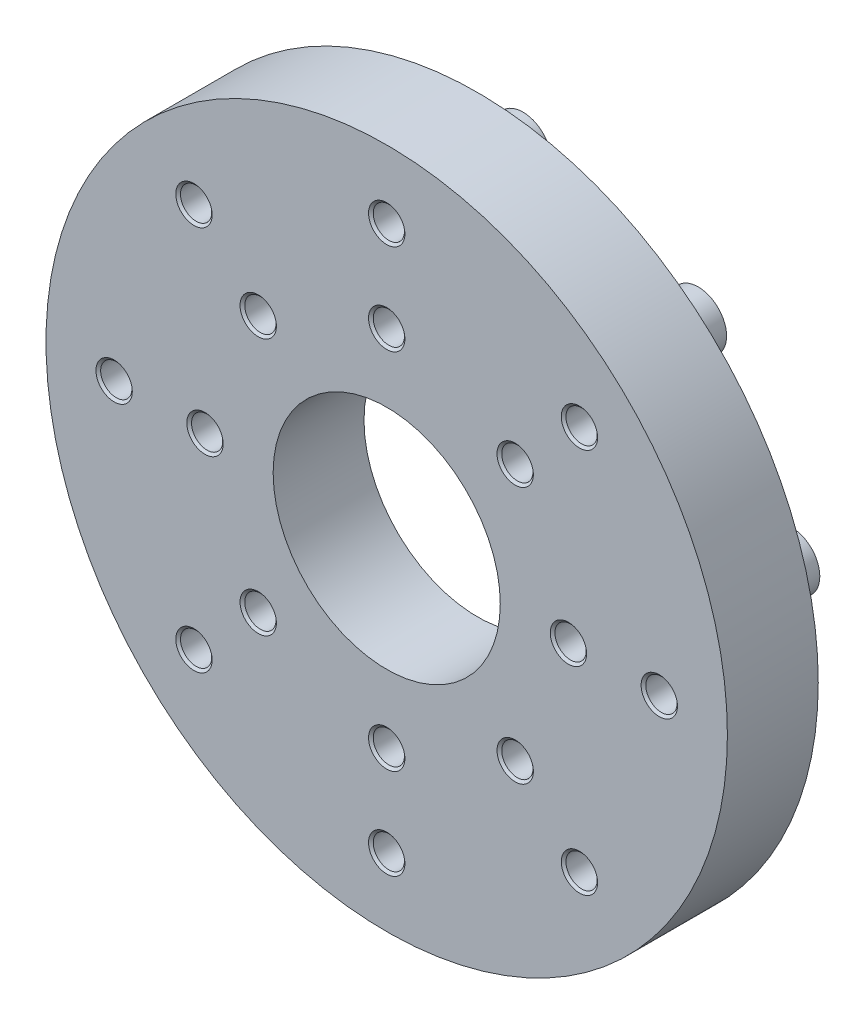
SolidWorks part; units mm, degrees
ref_plane "Front Plane" through (0, 0, 0) normal (0, 0, 1) x (1, 0, 0)
ref_plane "Top Plane" through (0, 0, 0) normal (0, 1, 0) x (1, 0, 0)
ref_plane "Right Plane" through (0, 0, 0) normal (1, 0, 0) x (0, 0, -1)
sketch "Sketch1" plane through (0, 0, 0) normal (0, 0, 1) x (1, 0, 0)
  circle A0 centre (0, 0) radius 190.5
extrude "Boss-Extrude1" add sketch "Sketch1" along normal blind 50.8
sketch "Sketch2" plane through (0, 0, 50.8) normal (0, 0, 1) x (1, 0, 0)
  circle A0 centre (0, 0) radius 63.5
extrude "Cut-Extrude1" cut sketch "Sketch2" against normal through all
sketch "Sketch3" plane through (0, 0, 50.8) normal (0, 0, 1) x (1, 0, 0)
  line L0 (0, 0) -> (0, 164.7437) construction
  circle A0 centre (0, 0) radius 101.6 construction
  circle A1 centre (0, 0) radius 152.4 construction
  point P4 (0, 152.4)
  point P6 (0, 101.6)
  point P7 (71.842, 71.842)
  point P8 (101.6, 0)
  point P9 (107.7631, 107.7631)
  point P11 (71.842, -71.842)
  point P12 (0, -101.6)
  point P13 (-71.842, -71.842)
  point P14 (-101.6, 0)
  point P15 (-71.842, 71.842)
  point P16 (0, 0)
  point P18 (152.4, 0)
  point P19 (107.7631, -107.7631)
  point P20 (0, -152.4)
  point P21 (-107.7631, -107.7631)
  point P22 (-152.4, 0)
  point P23 (-107.7631, 107.7631)
  point P24 (0, 0)
  dimension "D1" = 8
  dimension "D2" = 8
hole_wizard "3/4-16 Tapped Hole1" positions "Sketch3" profile "Sketch4" tap size "3/4-16" standard "ANSI Inch"
sketch "Sketch4" plane through (0, 0, 50.8) normal (1, 0, 0) x (0, -1, 0)
  line L0 (0, 0) -> (0, 48.1723)
  line L1 (0, 48.1723) -> (8.7312, 42.926)
  line L2 (8.7312, 42.926) -> (8.7312, 1.1989)
  line L3 (8.7312, 1.1989) -> (10.16, 0)
  line L5 (10.16, 0) -> (0, 0)
  line L6 (-8.7312, 1.1989) -> (-10.16, 0) construction
  line L10 (0, 48.1723) -> (-8.7313, 42.926) construction
  line L11 (0, -6.35) -> (0, 107.95) construction
  dimension "Tap Drill Dia." = 17.4625
  dimension "Tap Drill Depth" = 42.926
  dimension "Near C'Sink Dia." = 20.32
  dimension "Near C'Sink Angle" = 100
  dimension "Drill Angle" = 118
cosmetic thread "Hole Thread1" parameters "D1"=38.1, "D2"=19.05
cosmetic thread "Hole Thread2" parameters "D1"=38.1, "D2"=19.05
cosmetic thread "Hole Thread3" parameters "D1"=38.1, "D2"=19.05
cosmetic thread "Hole Thread4" parameters "D1"=38.1, "D2"=19.05
cosmetic thread "Hole Thread5" parameters "D1"=38.1, "D2"=19.05
cosmetic thread "Hole Thread6" parameters "D1"=38.1, "D2"=19.05
cosmetic thread "Hole Thread7" parameters "D1"=38.1, "D2"=19.05
cosmetic thread "Hole Thread8" parameters "D1"=38.1, "D2"=19.05
cosmetic thread "Hole Thread9" parameters "D1"=38.1, "D2"=19.05
cosmetic thread "Hole Thread10" parameters "D1"=38.1, "D2"=19.05
cosmetic thread "Hole Thread11" parameters "D1"=38.1, "D2"=19.05
cosmetic thread "Hole Thread12" parameters "D1"=38.1, "D2"=19.05
cosmetic thread "Hole Thread13" parameters "D1"=38.1, "D2"=19.05
cosmetic thread "Hole Thread14" parameters "D1"=38.1, "D2"=19.05
cosmetic thread "Hole Thread15" parameters "D1"=38.1, "D2"=19.05
cosmetic thread "Hole Thread16" parameters "D1"=38.1, "D2"=19.05
sketch "Sketch5" plane through (0, 0, 0) normal (0, 0, -1) x (-1, 0, 0)
  line L0 (0, 0) -> (0, 197.9064) construction
  circle A0 centre (0, 0) radius 152.4 construction
  circle A1 centre (0, 152.4) radius 15.875
  circle A2 centre (97.9608, 116.7452) radius 15.875
  circle A3 centre (150.0847, 26.464) radius 15.875
  circle A4 centre (131.9823, -76.2) radius 15.875
  circle A5 centre (52.1239, -143.2092) radius 15.875
  circle A6 centre (-52.1239, -143.2092) radius 15.875
  circle A7 centre (-131.9823, -76.2) radius 15.875
  circle A8 centre (-150.0847, 26.464) radius 15.875
  circle A9 centre (-97.9608, 116.7452) radius 15.875
  point P24 (0, 0)
  dimension "D1" = 9
extrude "Boss-Extrude2" add sketch "Sketch5" along normal blind 25.4
